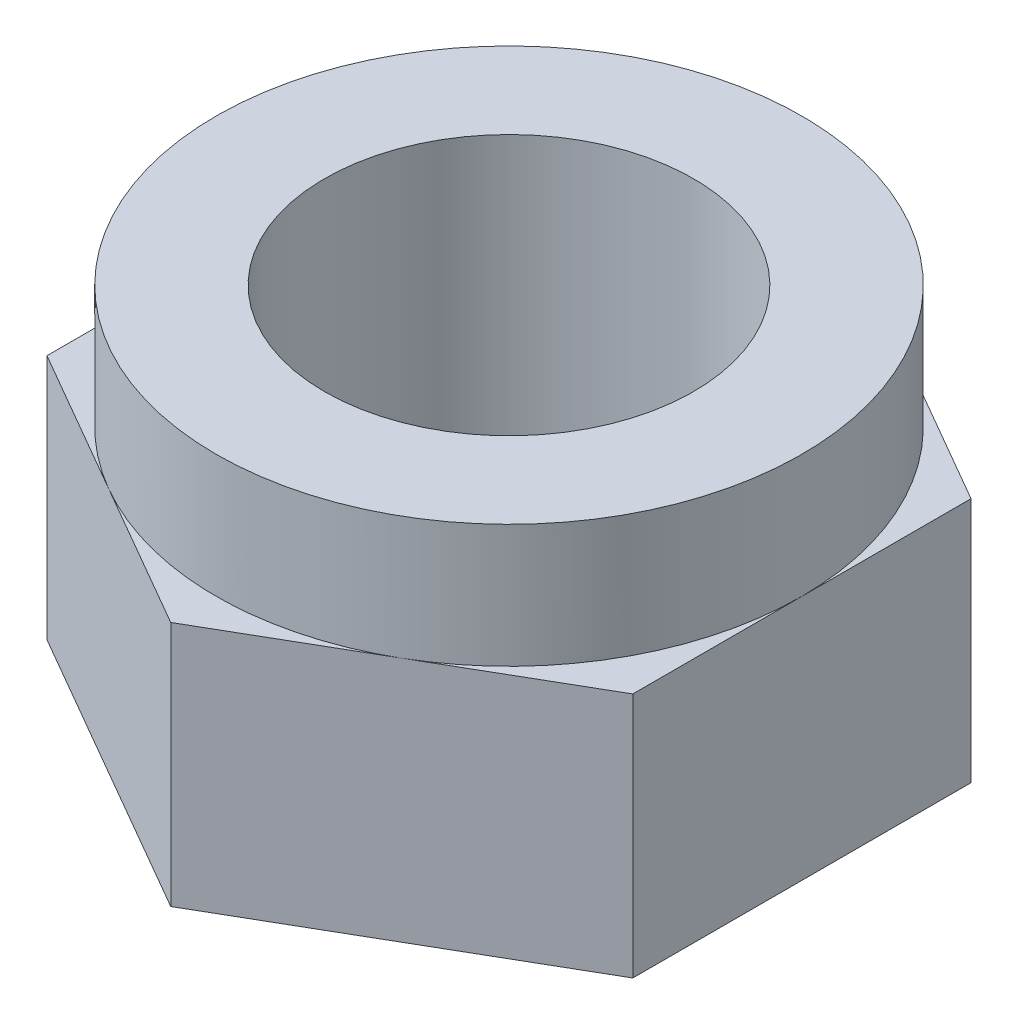
SolidWorks part; units mm, degrees
material "Stainless Steel (ferritic)"
ref_plane "Front Plane" through (0, 0, 0) normal (0, 0, 1) x (1, 0, 0)
ref_plane "Top Plane" through (0, 0, 0) normal (0, 1, 0) x (1, 0, 0)
ref_plane "Right Plane" through (0, 0, 0) normal (1, 0, 0) x (0, 0, -1)
sketch "Sketch1" plane through (0, 0, 0) normal (0, 1, 0) x (1, 0, 0)
  line L1 (0, 5.5) -> (-4.7631, 2.75)
  line L2 (-4.7631, 2.75) -> (-4.7631, -2.75)
  line L3 (-4.7631, -2.75) -> (0, -5.5)
  line L4 (0, -5.5) -> (4.7631, -2.75)
  line L5 (4.7631, -2.75) -> (4.7631, 2.75)
  line L6 (4.7631, 2.75) -> (0, 5.5)
  circle A0 centre (0, 0) radius 3
  circle A1 centre (0, 0) radius 4.7631 construction
  dimension "D1" = 6
  dimension "D2" = 11
extrude "Boss-Extrude1" add sketch "Sketch1" along normal blind 4
sketch "Sketch2" plane through (0, 4, 0) normal (0, 1, 0) x (1, 0, 0)
  line L0 (0, 5.5) -> (-4.7631, 2.75) construction
  circle A0 centre (0, 0) radius 4.7631
  circle A1 centre (0, 0) radius 3 construction
  circle A2 centre (0, 0) radius 3
extrude "Boss-Extrude2" add sketch "Sketch2" along normal blind 2
